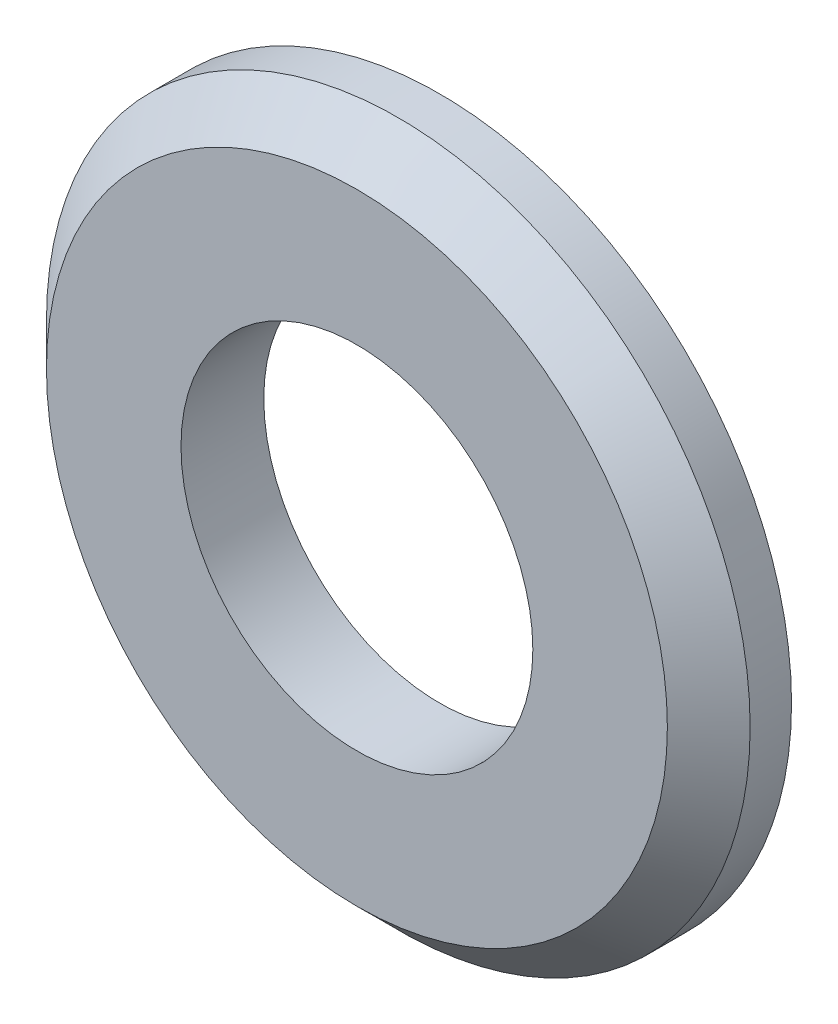
SolidWorks part; units mm, degrees
ref_plane "Alzado" through (0, 0, 0) normal (0, 0, 1) x (1, 0, 0)
ref_plane "Planta" through (0, 0, 0) normal (0, 1, 0) x (1, 0, 0)
ref_plane "Vista lateral" through (0, 0, 0) normal (1, 0, 0) x (0, 0, -1)
sketch "Croquis1" plane through (0, 0, 0) normal (0, 0, 1) x (1, 0, 0)
  circle A0 centre (0, 0) radius 4.25
  circle A1 centre (0, 0) radius 8.5
  dimension "D1" = 8.5
  dimension "D2" = 17
extrude "Saliente-Extruir1" add sketch "Croquis1" along normal blind 2
chamfer "Chaflán1" distance 1 angle 45 1 edges at (8.5, 0, 2)
